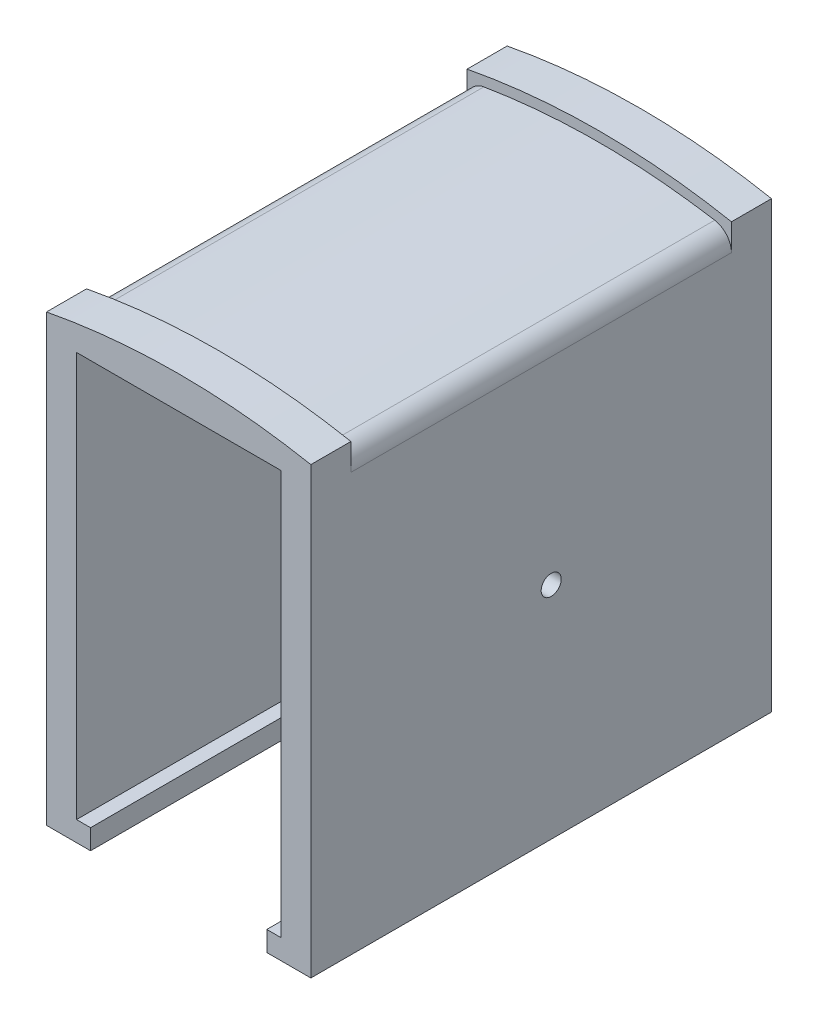
SolidWorks part; units mm, degrees
material "Polyester Resin"
ref_plane "Front Plane" through (0, 0, 0) normal (0, 0, 1) x (1, 0, 0)
ref_plane "Top Plane" through (0, 0, 0) normal (0, 1, 0) x (1, 0, 0)
ref_plane "Right Plane" through (0, 0, 0) normal (1, 0, 0) x (0, 0, -1)
sketch "Sketch1" plane through (0, 0, 0) normal (0, 0, 1) x (1, 0, 0)
  line L0 (-12.954, 0) -> (12.954, 0)
  line L1 (-12.954, 0) -> (-12.954, -51.308)
  line L2 (12.954, 0) -> (12.954, -51.308)
  line L3 (-12.954, -51.308) -> (-11.176, -51.308)
  line L4 (-11.176, -51.308) -> (-11.176, -53.848)
  line L5 (-11.176, -53.848) -> (-16.764, -53.848)
  line L6 (-16.764, -53.848) -> (-16.764, 1.27)
  line L7 (12.954, -51.308) -> (11.176, -51.308)
  line L8 (11.176, -51.308) -> (11.176, -53.848)
  line L9 (11.176, -53.848) -> (16.764, -53.848)
  line L10 (16.764, -53.848) -> (16.764, 1.27)
  arc A0 (-16.764, 1.27) -> (16.764, 1.27) centre (0, -86.0351) cw
  point P3 (0, 0)
  dimension "D10" = 88.9
  dimension "D11" = 1.778
  dimension "D1" = 25.908
  dimension "D2" = 51.308
  dimension "D3" = 51.308
  dimension "D4" = 2.54
  dimension "D5" = 5.588
  dimension "D6" = 1.27
  dimension "D7" = 2.54
  dimension "D8" = 5.588
  dimension "D9" = 1.27
  dimension "D12" = 1.778
extrude "Boss-Extrude1" add sketch "Sketch1" along normal mid plane 50.8
sketch "Sketch2" plane through (0, 0, 25.4) normal (0, 0, 1) x (1, 0, 0)
  line L0 (16.764, -53.848) -> (16.764, 2.54)
  line L1 (-16.764, -53.848) -> (-16.764, 2.54)
  line L11 (-12.954, -51.308) -> (-12.954, 0)
  line L12 (-12.954, 0) -> (12.954, 0)
  line L13 (12.954, 0) -> (12.954, -51.308)
  line L14 (12.954, -51.308) -> (11.176, -51.308)
  line L15 (11.176, -51.308) -> (11.176, -53.848)
  line L16 (11.176, -53.848) -> (16.764, -53.848)
  line L17 (16.764, -53.848) -> (16.764, 1.27)
  line L18 (-16.764, 1.27) -> (-16.764, -53.848)
  line L19 (-16.764, -53.848) -> (-11.176, -53.848)
  line L20 (-11.176, -53.848) -> (-11.176, -51.308)
  line L21 (-11.176, -51.308) -> (-12.954, -51.308)
  line L22 (-12.954, -51.308) -> (-12.954, 0)
  line L23 (-12.954, 0) -> (12.954, 0)
  line L24 (12.954, 0) -> (12.954, -51.308)
  line L25 (12.954, -51.308) -> (11.176, -51.308)
  line L26 (11.176, -51.308) -> (11.176, -53.848)
  line L27 (11.176, -53.848) -> (16.764, -53.848)
  line L30 (-16.764, -53.848) -> (-11.176, -53.848)
  line L31 (-11.176, -53.848) -> (-11.176, -51.308)
  line L32 (-11.176, -51.308) -> (-12.954, -51.308)
  arc A0 (-16.764, 2.54) -> (16.764, 2.54) centre (0, -84.7651) cw
  arc A1 (16.764, 1.27) -> (-16.764, 1.27) centre (0, -86.0351) ccw
  dimension "D2" = 1.27
  dimension "D4" = 88.9
  dimension "D3" = 1.27
  dimension "D1" = 0
extrude "Boss-Extrude2" add sketch "Sketch2" along normal blind 5.08
pattern_linear "LPattern1" count 2 spacing 53.34 along (0, 0, -1) of "Boss-Extrude2"
fillet "Fillet7" radius 2.54 2 edges at (16.764, 1.27, 1.27) (-16.764, 1.27, 1.27)
sketch "Sketch4" plane through (-16.764, 0, 0) normal (-1, 0, 0) x (0, 0, 1)
  line L1 (0, -18.4404) -> (0, 18.4404) construction
  line L2 (30.48, -51.308) -> (-27.94, -51.308) construction
  circle A0 centre (0, -25.908) radius 1.27
  point P4 (0, 0)
  point P7 (0, 0)
  dimension "D1" = 2.54
  dimension "D2" = 25.4
extrude "Cut-Extrude1" cut sketch "Sketch4" against normal through all
